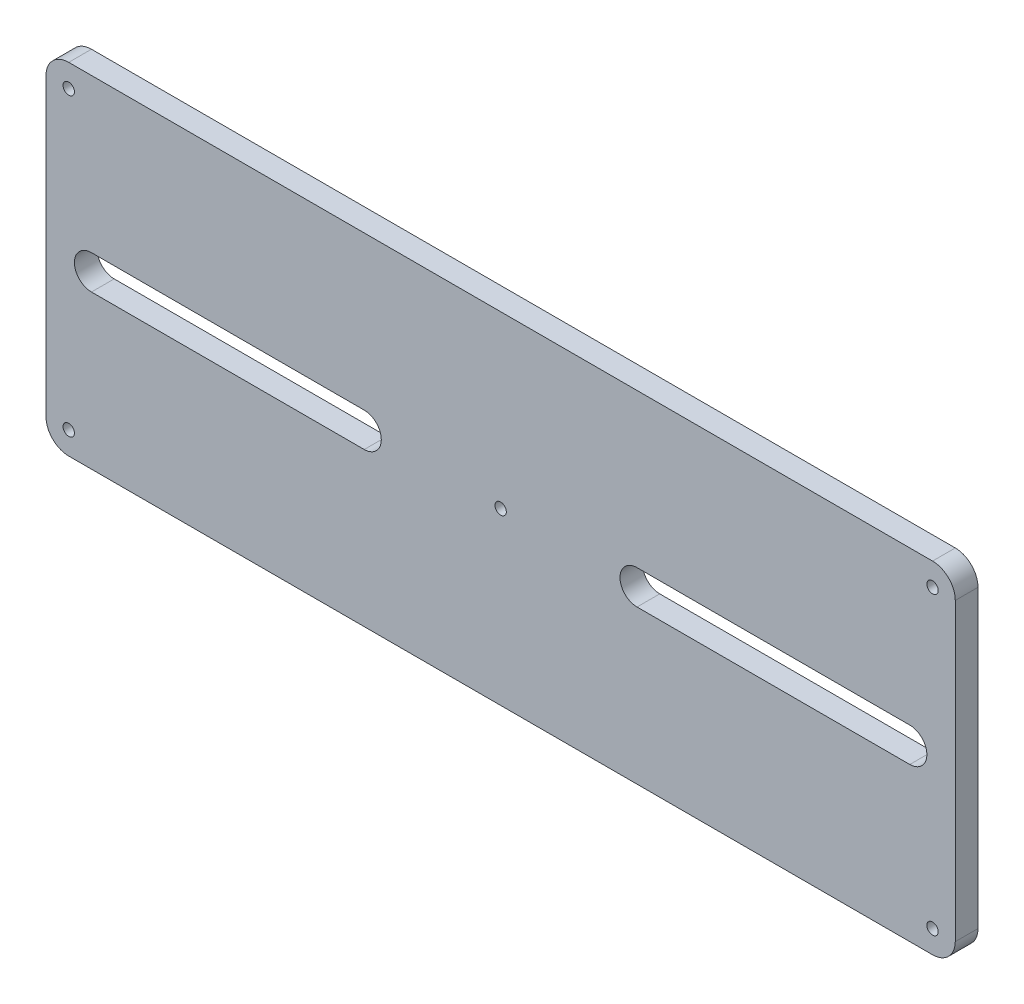
SolidWorks part; units mm, degrees
ref_plane "Front Plane" through (0, 0, 0) normal (0, 0, 1) x (1, 0, 0)
ref_plane "Top Plane" through (0, 0, 0) normal (0, 1, 0) x (1, 0, 0)
ref_plane "Right Plane" through (0, 0, 0) normal (1, 0, 0) x (0, 0, -1)
sketch "Sketch1" plane through (0, 0, 0) normal (0, 0, 1) x (1, 0, 0)
  line L0 (0, 0) -> (0, 45.2171) construction
  line L1 (-190, -75) -> (190, -75)
  line L2 (-200, -65) -> (-200, 65)
  line L3 (-190, 75) -> (190, 75)
  line L4 (200, -65) -> (200, 65)
  line L5 (-200, -75) -> (200, 75) construction
  line L6 (-200, 75) -> (200, -75) construction
  line L7 (0, 0) -> (-62.4213, 0) construction
  arc A0 (-190, -75) -> (-200, -65) centre (-190, -65) cw
  arc A1 (190, -75) -> (200, -65) centre (190, -65) ccw
  arc A2 (190, 75) -> (200, 65) centre (190, 65) cw
  arc A3 (-200, 65) -> (-190, 75) centre (-190, 65) cw
  circle A4 centre (-190, 65) radius 2.5
  circle A5 centre (-190, -65) radius 2.5
  circle A6 centre (190, -65) radius 2.5
  circle A7 centre (190, 65) radius 2.5
  point P0 (0, 0)
  dimension "D3" = 10
  dimension "D4" = 5
  dimension "D1" = 400
  dimension "D2" = 150
extrude "Boss-Extrude1" add sketch "Sketch1" along normal blind 10
sketch "Sketch2" plane through (0, 0, 10) normal (0, 0, 1) x (1, 0, 0)
  line L0 (0, 0) -> (0, 28.5712) construction
  line L1 (0, 0) -> (-120, 0) construction
  line L2 (-60, 0) -> (-180, 0) construction
  line L3 (-60, -7.5) -> (-180, -7.5)
  line L4 (-60, 7.5) -> (-180, 7.5)
  line L5 (60, 0) -> (180, 0) construction
  line L6 (60, -7.5) -> (180, -7.5)
  line L7 (60, 7.5) -> (180, 7.5)
  arc A0 (-60, -7.5) -> (-60, 7.5) centre (-60, 0) ccw
  arc A1 (-180, 7.5) -> (-180, -7.5) centre (-180, 0) ccw
  arc A2 (60, -7.5) -> (60, 7.5) centre (60, 0) cw
  arc A3 (180, 7.5) -> (180, -7.5) centre (180, 0) cw
  circle A4 centre (0, 0) radius 2.5
  point P6 (-120, 0)
  point P13 (120, 0)
  dimension "D4" = 5
  dimension "D1" = 120
  dimension "D2" = 15
  dimension "D3" = 120
extrude "Cut-Extrude1" cut sketch "Sketch2" against normal blind 10
